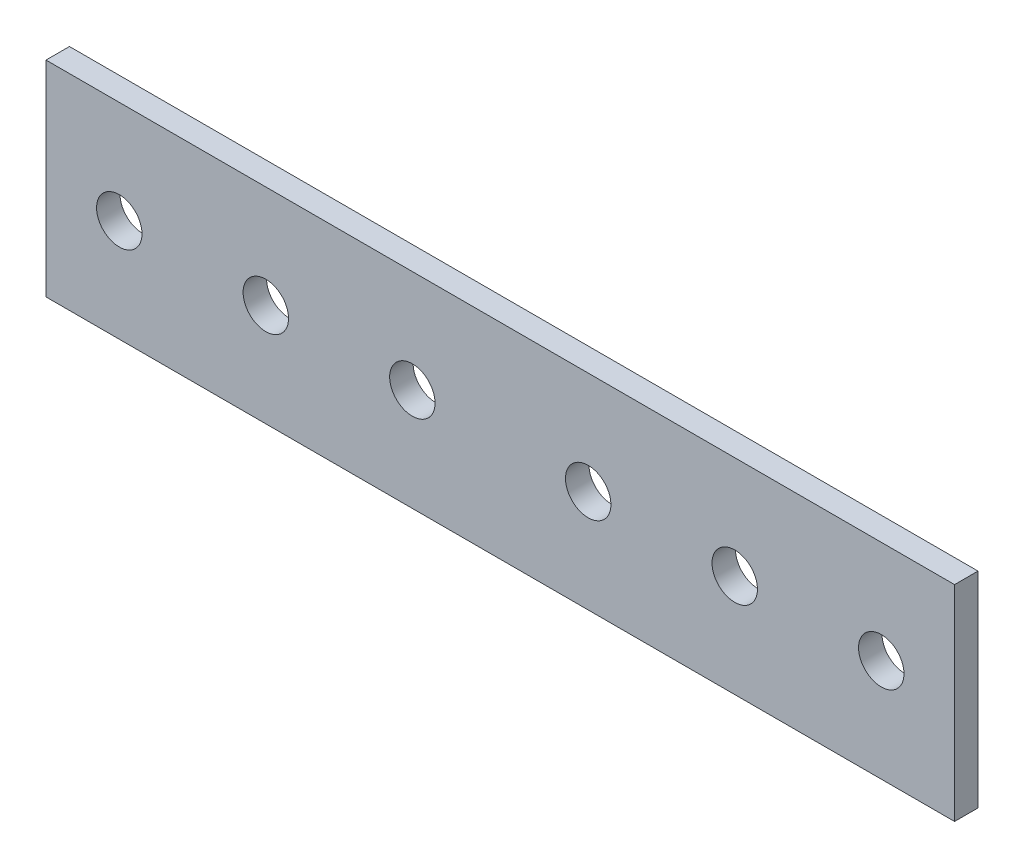
SolidWorks part; units mm, degrees
ref_plane "前视基准面" through (0, 0, 0) normal (0, 0, 1) x (1, 0, 0)
ref_plane "上视基准面" through (0, 0, 0) normal (0, 1, 0) x (1, 0, 0)
ref_plane "右视基准面" through (0, 0, 0) normal (1, 0, 0) x (0, 0, -1)
sketch "草图1" plane through (0, 0, 0) normal (0, 0, 1) x (1, 0, 0)
  line L0 (265.0907, -875.9782) -> (265.0907, 49124.0218) construction
  line L1 (-44.9093, 124.0218) -> (575.0907, 124.0218)
  line L2 (-44.9093, 124.0218) -> (-44.9093, -15.9782)
  line L3 (-44.9093, -15.9782) -> (575.0907, -15.9782)
  line L4 (575.0907, 124.0218) -> (575.0907, -15.9782)
  line L5 (-1044.9093, 54.0218) -> (48955.0907, 54.0218) construction
  circle A0 centre (5.0907, 54.0218) radius 15.5
  circle A1 centre (205.0907, 54.0218) radius 15.5
  circle A2 centre (105.0907, 54.0218) radius 15.5
  circle A3 centre (425.0907, 54.0218) radius 15.5
  circle A4 centre (325.0907, 54.0218) radius 15.5
  circle A5 centre (525.0907, 54.0218) radius 15.5
  point P9 (-44.9093, 54.0218)
  dimension "D5" = 31
  dimension "D6" = 31
  dimension "D8" = 31
  dimension "D1" = 140
  dimension "D2" = 620
  dimension "D3" = 310
  dimension "D4" = 50
  dimension "D7" = 200
  dimension "D9" = 100
extrude "拉伸1" add sketch "草图1" along normal blind 16
